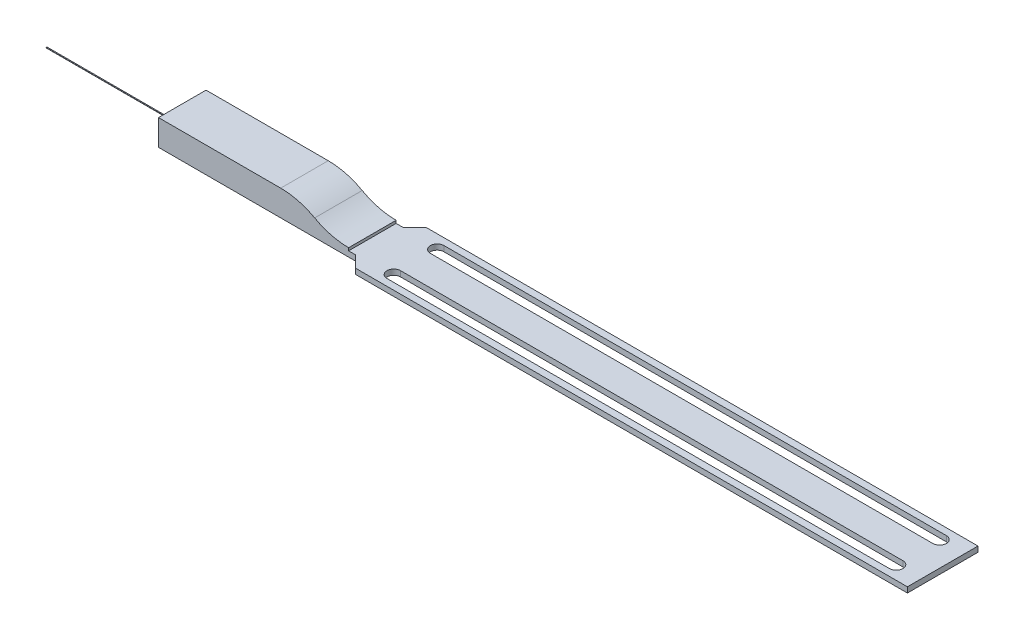
SolidWorks part; units mm, degrees
ref_plane "Front Plane" through (0, 0, 0) normal (0, 0, 1) x (1, 0, 0)
ref_plane "Top Plane" through (0, 0, 0) normal (0, 1, 0) x (1, 0, 0)
ref_plane "Right Plane" through (0, 0, 0) normal (1, 0, 0) x (0, 0, -1)
sketch "Sketch1" plane through (0, 0, 0) normal (0, 1, 0) x (1, 0, 0)
  line L1 (-7, -1.75) -> (7, -1.75)
  line L2 (-7, -1.75) -> (-7, 1.75)
  line L3 (-7, 1.75) -> (7, 1.75)
  line L4 (7, -1.75) -> (7, 1.75)
  line L5 (-7, -1.75) -> (7, 1.75) construction
  line L6 (-7, 1.75) -> (7, -1.75) construction
  point P0 (0, 0)
  dimension "D1" = 14
  dimension "D2" = 3.5
extrude "Boss-Extrude1" add sketch "Sketch1" along normal blind 1.9
sketch "Sketch2" plane through (0, 0, 0) normal (0, -1, 0) x (1, 0, 0)
  line L0 (7, -1.75) -> (7.5, -1.75)
  line L1 (7.5, -1.75) -> (8.35, -2.6)
  line L2 (8.35, -2.6) -> (49, -2.6)
  line L3 (7, 1.75) -> (7.5, 1.75)
  line L4 (7.5, 1.75) -> (8.35, 2.6)
  line L5 (8.35, 2.6) -> (49, 2.6)
  line L6 (7.5, 1.75) -> (7.5, -1.75) construction
  line L7 (8.35, -1.75) -> (8.35, 1.75) construction
  line L8 (7.5, 1.75) -> (8.35, 1.75) construction
  line L9 (7.5, -1.75) -> (8.35, -1.75) construction
  line L10 (8.35, -1.75) -> (8.35, -2.6) construction
  line L11 (8.35, 1.75) -> (8.35, 2.6) construction
  line L12 (7, 1.75) -> (7, -1.75)
  line L13 (7, 0) -> (49, 0) construction
  line L14 (49, 2.6) -> (49, -2.6)
  line L15 (47.175, 1.6) -> (10.175, 1.6) construction
  line L16 (47.175, 1.1) -> (10.175, 1.1)
  line L17 (47.175, 2.1) -> (10.175, 2.1)
  line L18 (47.175, -1.6) -> (10.175, -1.6) construction
  line L19 (47.175, -2.1) -> (10.175, -2.1)
  line L20 (47.175, -1.1) -> (10.175, -1.1)
  line L21 (28.675, 2.6) -> (28.675, 1.6) construction
  line L22 (28.675, 1.6) -> (28.675, -1.6) construction
  line L23 (28.675, -1.6) -> (28.675, -2.6) construction
  arc A0 (47.175, 1.1) -> (47.175, 2.1) centre (47.175, 1.6) ccw
  arc A1 (10.175, 2.1) -> (10.175, 1.1) centre (10.175, 1.6) ccw
  arc A2 (47.175, -2.1) -> (47.175, -1.1) centre (47.175, -1.6) ccw
  arc A3 (10.175, -1.1) -> (10.175, -2.1) centre (10.175, -1.6) ccw
  point P15 (28.675, 1.6)
  point P21 (28.675, -1.6)
  dimension "D2" = 0.5
  dimension "D1" = 42
  dimension "D3" = 37
  dimension "D4" = 1
  dimension "D5" = 5.2
  dimension "D6" = 0.5
extrude "Boss-Extrude2" add sketch "Sketch2" against normal blind 0.4
sketch "Sketch3" plane through (0, 0, 0) normal (0, 0, 1) x (1, 0, 0)
  line L0 (7, 0.6) -> (7, 1.9)
  line L1 (7, 1.9) -> (7, 0.4) construction
  line L2 (7, 1.9) -> (2, 1.9)
  line L3 (-7, 1.9) -> (7, 1.9) construction
  line L4 (7, 0.6) -> (2, 0.6) construction
  line L5 (2, 0.6) -> (2, 1.9) construction
  line L7 (7, 0.6) -> (7, 0) construction
  line L8 (2.86, 0) -> (-2.86, 0) construction
  arc A0 (2, 1.9) -> (4.5, 1.25) centre (2, -3.2327) cw
  arc A1 (4.5, 1.25) -> (7, 0.6) centre (7, 5.7327) ccw
  dimension "D1" = 5
  dimension "D2" = 0.6
extrude "Cut-Extrude1" cut sketch "Sketch3" against normal through all both and the other way through all
sketch "Sketch4" plane through (-7, 0, 0) normal (-1, 0, 0) x (0, 0, 1)
  line L5 (-0.035, 0.488) -> (0.035, 0.488)
  line L6 (-0.035, 0.488) -> (-0.035, 0.512)
  line L11 (-0.035, 0.512) -> (0.035, 0.512)
  line L12 (0.035, 0.488) -> (0.035, 0.512)
  line L13 (0, 0) -> (0, 0.5) construction
  line L14 (-1.75, 0) -> (1.75, 0) construction
  line L15 (-0.035, 0.488) -> (0.035, 0.512) construction
  line L16 (-0.035, 0.512) -> (0.035, 0.488) construction
  dimension "D1" = 0.07
  dimension "D2" = 0.024
extrude "Boss-Extrude3" add sketch "Sketch4" along normal blind 10
